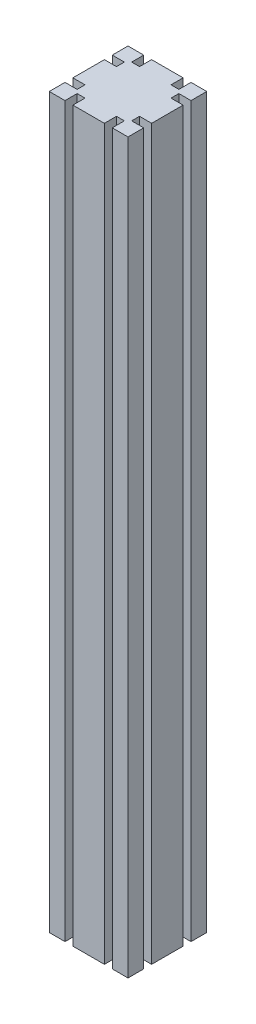
SolidWorks part; units mm, degrees
ref_plane "Front Plane" through (0, 0, 0) normal (0, 0, 1) x (1, 0, 0)
ref_plane "Top Plane" through (0, 0, 0) normal (0, 1, 0) x (1, 0, 0)
ref_plane "Right Plane" through (0, 0, 0) normal (1, 0, 0) x (0, 0, -1)
sketch "Sketch1" plane through (0, 0, 0) normal (0, 1, 0) x (1, 0, 0)
  line L0 (56.6792, 50.48) -> (48.6792, 50.48)
  line L1 (-7.3208, 50.48) -> (8.6792, 50.48)
  line L2 (16.6792, 50.48) -> (48.6792, 50.48)
  line L3 (56.6792, 50.48) -> (72.6792, 50.48)
  line L4 (8.6792, 50.48) -> (16.6792, 50.48)
  line L5 (8.6792, 50.48) -> (8.6792, 38.18)
  line L6 (16.6792, 38.18) -> (8.6792, 38.18)
  line L7 (8.6792, 38.18) -> (8.6792, 50.48)
  line L8 (16.6792, 38.18) -> (16.6792, 50.48)
  line L9 (48.6792, 50.48) -> (48.6792, 38.18)
  line L10 (48.6792, 38.18) -> (56.6792, 38.18)
  line L11 (56.6792, 38.18) -> (56.6792, 50.48)
  line L12 (48.6792, 50.48) -> (48.6792, 38.18)
  line L13 (-7.3208, 50.48) -> (8.6792, 50.48)
  line L14 (72.6792, 50.48) -> (72.6792, 34.48)
  line L15 (72.6792, 34.48) -> (60.3792, 34.48)
  line L17 (60.3792, 34.48) -> (60.3792, 26.48)
  line L19 (60.3792, 26.48) -> (72.6792, 26.48)
  line L21 (72.6792, 26.48) -> (72.6792, -5.52)
  line L22 (72.6792, -5.52) -> (60.3792, -5.52)
  line L23 (60.3792, -5.52) -> (60.3792, -13.52)
  line L24 (60.3792, -13.52) -> (72.6792, -13.52)
  line L28 (72.6792, -13.52) -> (72.6792, -29.52)
  line L29 (72.6792, -29.52) -> (56.6792, -29.52)
  line L30 (56.6792, -29.52) -> (56.6792, -17.22)
  line L31 (56.6792, -17.22) -> (48.6792, -17.22)
  line L32 (48.6792, -17.22) -> (48.6792, -29.52)
  line L33 (48.6792, -29.52) -> (16.6792, -29.52)
  line L34 (16.6792, -29.52) -> (16.6792, -17.22)
  line L35 (16.6792, -17.22) -> (8.6792, -17.22)
  line L36 (8.6792, -17.22) -> (8.6792, -29.52)
  line L37 (8.6792, -29.52) -> (-7.3208, -29.52)
  line L38 (-7.3208, -29.52) -> (-7.3208, -13.52)
  line L39 (-7.3208, -13.52) -> (4.9792, -13.52)
  line L40 (4.9792, -13.52) -> (4.9792, -5.52)
  line L41 (4.9792, -5.52) -> (-7.3208, -5.52)
  line L42 (-7.3208, -5.52) -> (-7.3208, 26.48)
  line L43 (-7.3208, 26.48) -> (4.9792, 26.48)
  line L44 (4.9792, 26.48) -> (4.9792, 34.48)
  line L45 (4.9792, 34.48) -> (-7.3208, 34.48)
  line L46 (-7.3208, 34.48) -> (-7.3208, 50.48)
  point P0 (12.6792, 38.18)
  point P7 (52.6792, 38.18)
  dimension "D1" = 80
  dimension "D2" = 40
  dimension "D3" = 8
  dimension "D4" = 12.3
extrude "Boss-Extrude1" add sketch "Sketch1" along normal blind 740 contours L46 L45 L44 L43 L42 L41 L40 L39 L38 L37 L36 L35 L34 L33 L32 L31 L30 L29 L28 L24 L23 L22 L21 L19 L17 L15 L14 L3 L11 L10 L9 L2 L8 L6 L5 L1
